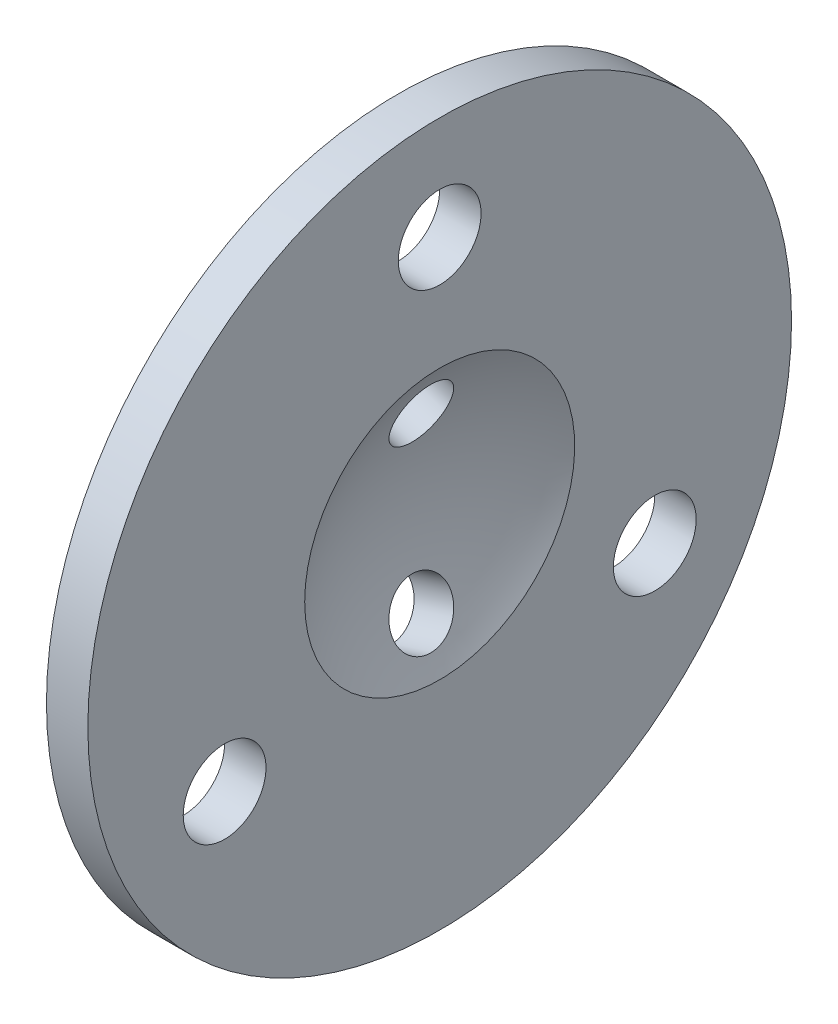
SolidWorks part; units mm, degrees
material "6061 合金"
ref_plane "前视基准面" through (0, 0, 0) normal (0, 0, 1) x (1, 0, 0)
ref_plane "上视基准面" through (0, 0, 0) normal (0, 1, 0) x (1, 0, 0)
ref_plane "右视基准面" through (0, 0, 0) normal (1, 0, 0) x (0, 0, -1)
sketch "草图1" plane through (0, 0, 0) normal (0, 0, 1) x (1, 0, 0)
  line L0 (-26.1552, 0) -> (18.822, 0) construction
  line L1 (0, 25.0552) -> (0, -21.2256) construction
  line L2 (-14.3875, 7) -> (-14.3875, -7) construction
  line L3 (-12.3875, -6.523) -> (-12.3875, -17) construction
  line L4 (-14.3875, 17) -> (-12.3875, 17)
  line L5 (-14.3875, 17) -> (-14.3875, 7)
  line L6 (-14.3875, -17) -> (-12.3875, -17) construction
  line L7 (-12.3875, 17) -> (-12.3875, 6.523)
  line L8 (-14.3875, -7) -> (-14.3875, -17) construction
  line L9 (-16, 0) -> (-14, 0)
  arc A0 (-14.3875, 7) -> (-14.3875, -7) centre (0, 0) ccw construction
  arc A1 (-12.3875, 6.523) -> (-12.3875, -6.523) centre (0, 0) ccw construction
  arc A2 (-12.3875, 6.523) -> (-14, 0) centre (0, 0) ccw
  arc A3 (-14.3875, 7) -> (-16, 0) centre (0, 0) ccw
  dimension "D3" = 32
  dimension "D4" = 28
  dimension "D1" = 14
  dimension "D2" = 2
  dimension "D5" = 34
revolve "旋转3" add sketch "草图1" angle 360 about L0
sketch "草图2" plane through (0, 0, 0) normal (0, 0, 1) x (1, 0, 0)
  line L0 (0, 0) -> (-25.7781, 0) construction
  line L1 (0, 0) -> (-29.9996, 9.4588) construction
  line L2 (-10.9935, 5.039) -> (-18.6233, 7.4447)
  line L3 (-19.0743, 6.0141) -> (-11.4446, 3.6085)
  line L4 (-18.6233, 7.4447) -> (-19.0743, 6.0141)
  line L5 (-11.4446, 3.6085) -> (-10.9935, 5.039)
  dimension "D1" = 17.5
  dimension "D2" = 1.5
  dimension "D3" = 12
  dimension "D4" = 20
revolve "切除-旋转1" cut sketch "草图2" angle 360 about L1
mirror "镜向1" about plane through (0, 0, 0) normal (0, 1, 0) of "切除-旋转1"
sketch "草图3" plane through (-14.3875, 0, 0) normal (-1, 0, 0) x (0, 0, 1)
  line L0 (0, 18.2074) -> (0, 0) construction
  circle A0 centre (0, 0) radius 12 construction
  circle A1 centre (0, 12) radius 2
  circle A2 centre (10.3923, -6) radius 2
  circle A3 centre (-10.3923, -6) radius 2
  point P13 (0, 0)
  dimension "D1" = 24
  dimension "D2" = 4
  dimension "D3" = 3
extrude "切除-拉伸1" cut sketch "草图3" against normal blind 10
